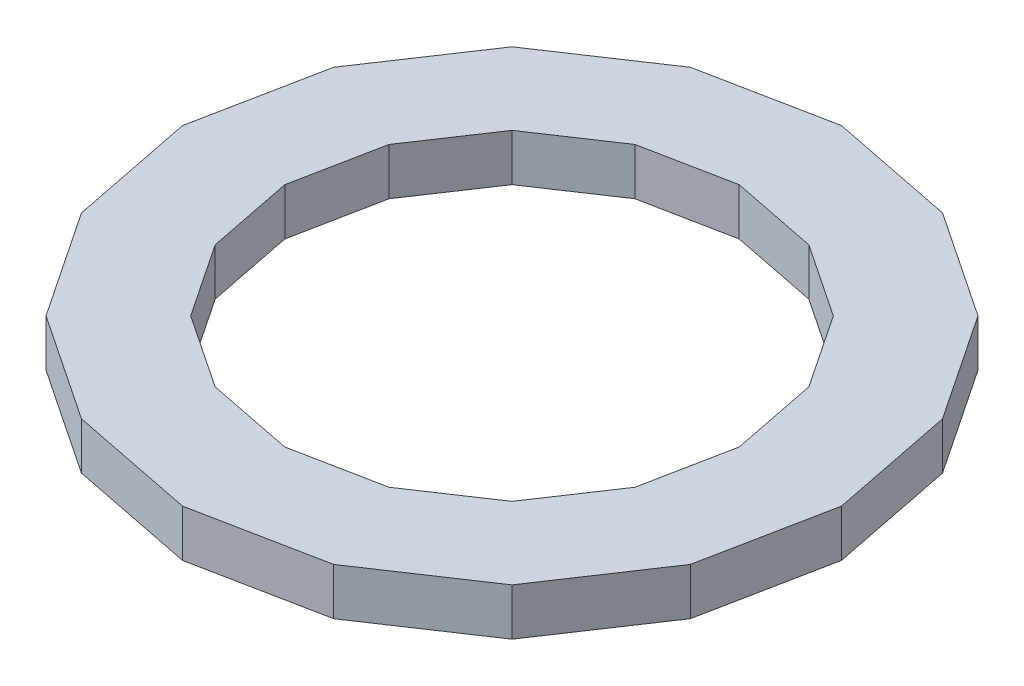
SolidWorks part; units mm, degrees
ref_plane "Front Plane" through (0, 0, 0) normal (0, 0, 1) x (1, 0, 0)
ref_plane "Top Plane" through (0, 0, 0) normal (0, 1, 0) x (1, 0, 0)
ref_plane "Right Plane" through (0, 0, 0) normal (1, 0, 0) x (0, 0, -1)
sketch "Sketch1" plane through (0, 0, 0) normal (0, 1, 0) x (1, 0, 0)
  line L1 (92.0148, 0) -> (85.0106, 35.2125)
  line L2 (85.0106, 35.2125) -> (65.0643, 65.0643)
  line L3 (65.0643, 65.0643) -> (35.2125, 85.0106)
  line L4 (35.2125, 85.0106) -> (0, 92.0148)
  line L5 (0, 92.0148) -> (-35.2125, 85.0106)
  line L6 (-35.2125, 85.0106) -> (-65.0643, 65.0643)
  line L7 (-65.0643, 65.0643) -> (-85.0106, 35.2125)
  line L8 (-85.0106, 35.2125) -> (-92.0148, 0)
  line L9 (-92.0148, 0) -> (-85.0106, -35.2125)
  line L10 (-85.0106, -35.2125) -> (-65.0643, -65.0643)
  line L11 (-65.0643, -65.0643) -> (-35.2125, -85.0106)
  line L12 (-35.2125, -85.0106) -> (0, -92.0148)
  line L13 (0, -92.0148) -> (35.2125, -85.0106)
  line L14 (35.2125, -85.0106) -> (65.0643, -65.0643)
  line L15 (65.0643, -65.0643) -> (85.0106, -35.2125)
  line L16 (85.0106, -35.2125) -> (92.0148, 0)
  line L17 (133.451, 0) -> (123.2927, 51.0695)
  line L18 (123.2927, 51.0695) -> (94.3641, 94.3641)
  line L19 (94.3641, 94.3641) -> (51.0695, 123.2927)
  line L20 (51.0695, 123.2927) -> (0, 133.451)
  line L21 (0, 133.451) -> (-51.0695, 123.2927)
  line L22 (-51.0695, 123.2927) -> (-94.3641, 94.3641)
  line L23 (-94.3641, 94.3641) -> (-123.2927, 51.0695)
  line L24 (-123.2927, 51.0695) -> (-133.451, 0)
  line L25 (-133.451, 0) -> (-123.2927, -51.0695)
  line L26 (-123.2927, -51.0695) -> (-94.3641, -94.3641)
  line L27 (-94.3641, -94.3641) -> (-51.0695, -123.2927)
  line L28 (-51.0695, -123.2927) -> (0, -133.451)
  line L29 (0, -133.451) -> (51.0695, -123.2927)
  line L30 (51.0695, -123.2927) -> (94.3641, -94.3641)
  line L31 (94.3641, -94.3641) -> (123.2927, -51.0695)
  line L32 (123.2927, -51.0695) -> (133.451, 0)
  circle A0 centre (0, 0) radius 90.2468 construction
  circle A1 centre (0, 0) radius 130.8868 construction
  dimension "D1" = 52.07
  dimension "D2" = 40.64
extrude "Boss-Extrude1" add sketch "Sketch1" along normal blind 19.05
